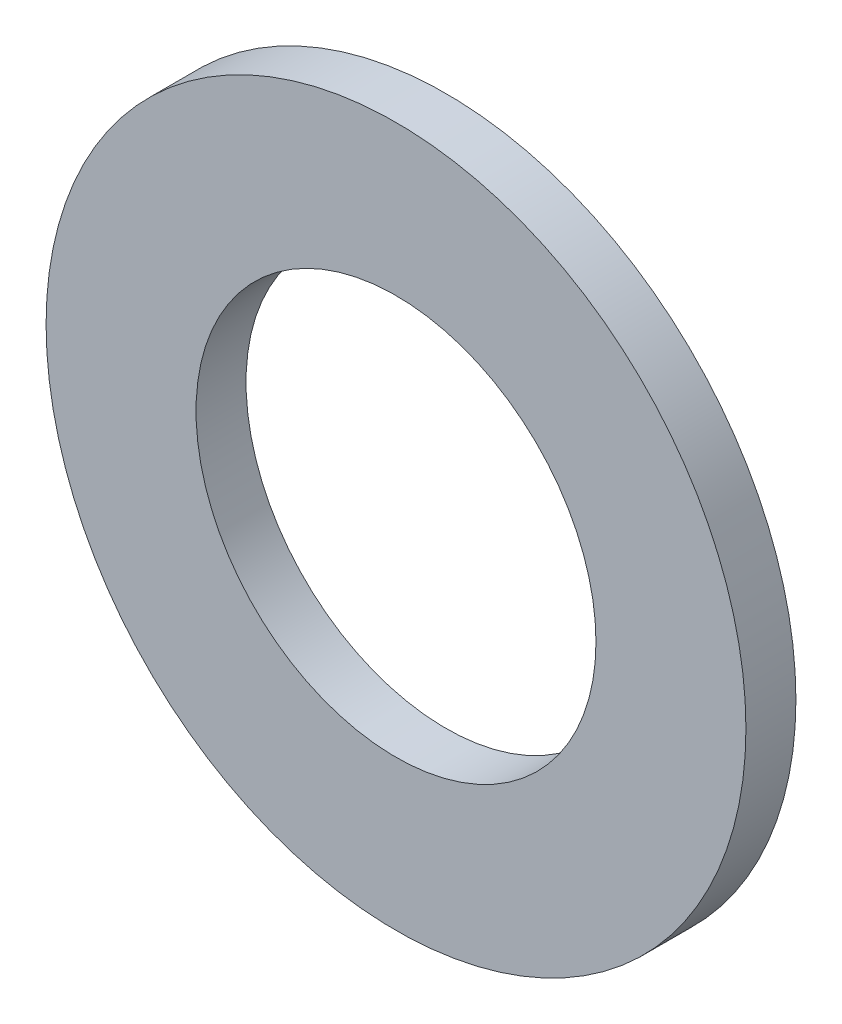
SolidWorks part; units mm, degrees
material "AISI 304"
ref_plane "前视基准面" through (0, 0, 0) normal (0, 0, 1) x (1, 0, 0)
ref_plane "上视基准面" through (0, 0, 0) normal (0, 1, 0) x (1, 0, 0)
ref_plane "右视基准面" through (0, 0, 0) normal (1, 0, 0) x (0, 0, -1)
sketch "草图1" plane through (0, 0, 0) normal (0, 0, 1) x (1, 0, 0)
  circle A0 centre (0, 0) radius 3.5
  circle A1 centre (0, 0) radius 2
  dimension "D1" = 4
  dimension "D2" = 7
extrude "凸台-拉伸1" add sketch "草图1" along normal blind 0.5
